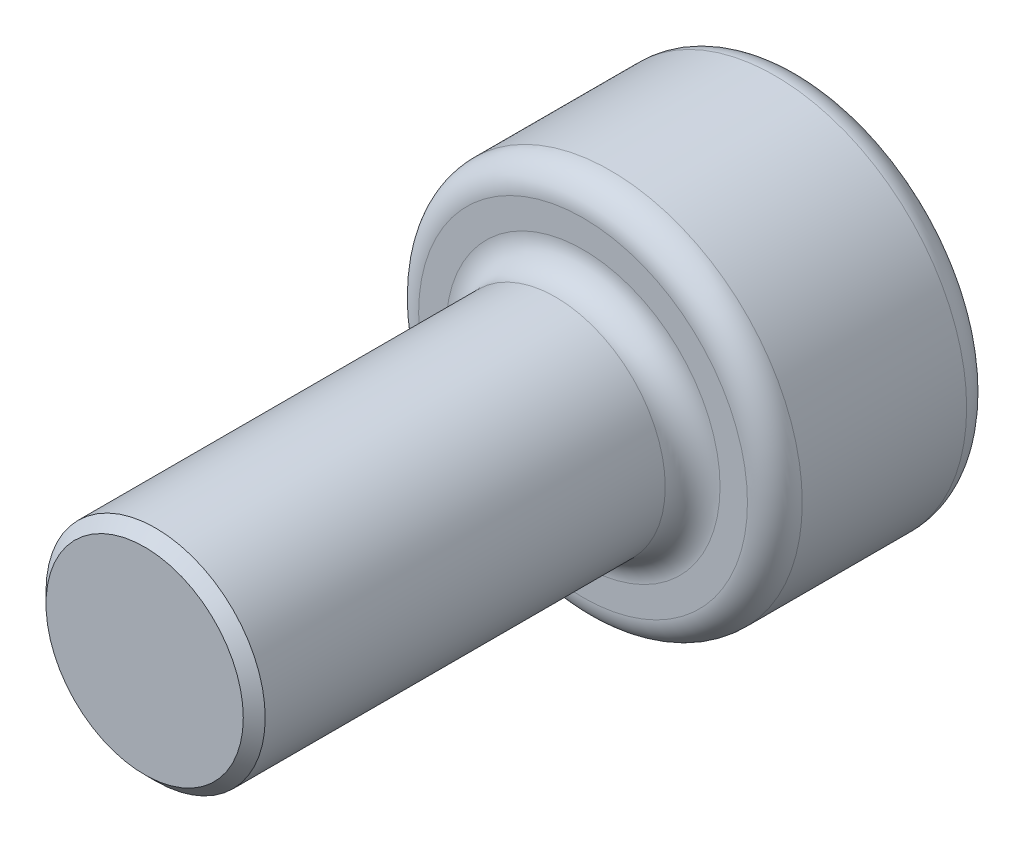
SolidWorks part; units mm, degrees
material "AISI 4340 Steel, annealed"
ref_plane "Front Plane" through (0, 0, 0) normal (0, 0, 1) x (1, 0, 0)
ref_plane "Top Plane" through (0, 0, 0) normal (0, 1, 0) x (1, 0, 0)
ref_plane "Right Plane" through (0, 0, 0) normal (1, 0, 0) x (0, 0, -1)
sketch "Sketch1" plane through (0, 0, 0) normal (0, 0, 1) x (1, 0, 0)
  circle A0 centre (0, 0) radius 3.5
  dimension "D1" = 7
extrude "Boss-Extrude1" add sketch "Sketch1" along normal blind 4
sketch "Sketch2" plane through (0, 0, 4) normal (0, 0, 1) x (1, 0, 0)
  circle A0 centre (0, 0) radius 2
  dimension "D1" = 4
extrude "Boss-Extrude2" add sketch "Sketch2" along normal blind 8
sketch "Sketch3" plane through (0, 0, 0) normal (0, 0, -1) x (-1, 0, 0)
  line L1 (2.0207, 0) -> (1.0104, 1.75)
  line L2 (1.0104, 1.75) -> (-1.0104, 1.75)
  line L3 (-1.0104, 1.75) -> (-2.0207, 0)
  line L4 (-2.0207, 0) -> (-1.0104, -1.75)
  line L5 (-1.0104, -1.75) -> (1.0104, -1.75)
  line L6 (1.0104, -1.75) -> (2.0207, 0)
  circle A0 centre (0, 0) radius 1.75 construction
  dimension "D1" = 3.5
extrude "Cut-Extrude1" cut sketch "Sketch3" against normal blind 2.5
fillet "Fillet1" radius 0.5 9 edges at (3.5, 0, 4) (2, 0, 4) (3.5, 0, 0) (0, 1.75, 0) (1.5155, 0.875, 0) (1.5155, -0.875, 0) (0, -1.75, 0) (-1.5155, -0.875, 0) (-1.5155, 0.875, 0)
chamfer "Chamfer1" distance 0.2 angle 45 1 edges at (2, 0, 12)
sketch "Sketch4" plane through (0, 0, 4) normal (0, 0, 1) x (1, 0, 0)
  circle A0 centre (0, 0) radius 6
  dimension "D1" = 12
extrude "Boss-Extrude3" [suppressed] add sketch "Sketch4" along normal blind 0.8
fillet "Fillet2" [suppressed] radius 0.1
